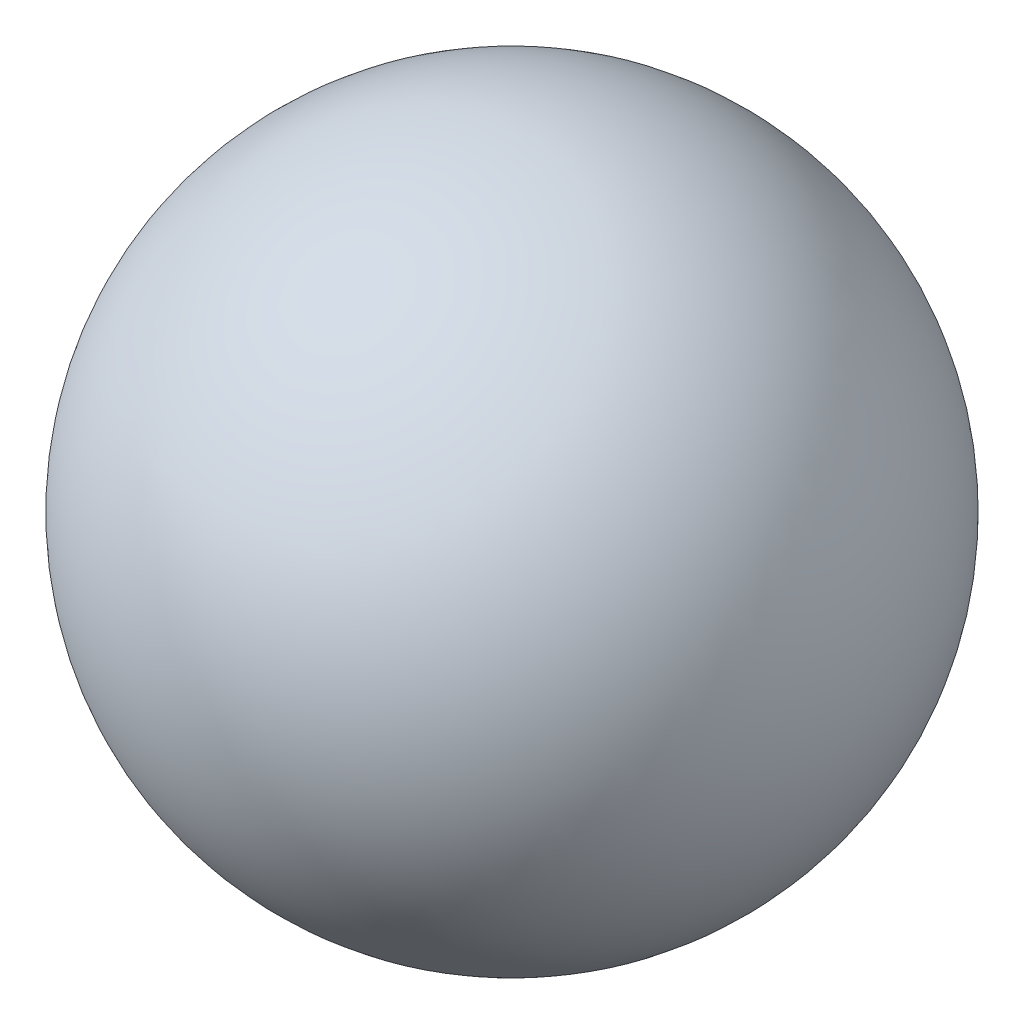
SolidWorks part; units mm, degrees
ref_plane "Alzado" through (0, 0, 0) normal (0, 0, 1) x (1, 0, 0)
ref_plane "Planta" through (0, 0, 0) normal (0, 1, 0) x (1, 0, 0)
ref_plane "Vista lateral" through (0, 0, 0) normal (1, 0, 0) x (0, 0, -1)
sketch "Croquis1" plane through (0, 0, 0) normal (0, 0, 1) x (1, 0, 0)
  line L0 (0, -0.15) -> (0, 0.0165) construction
  line L1 (0, 0.3) -> (0, -0.3)
  arc A0 (0, -0.3) -> (0, 0.3) centre (0, 0) ccw
  dimension "D1" = 0.6
revolve "Revolución1" add sketch "Croquis1" angle 360 about L0
